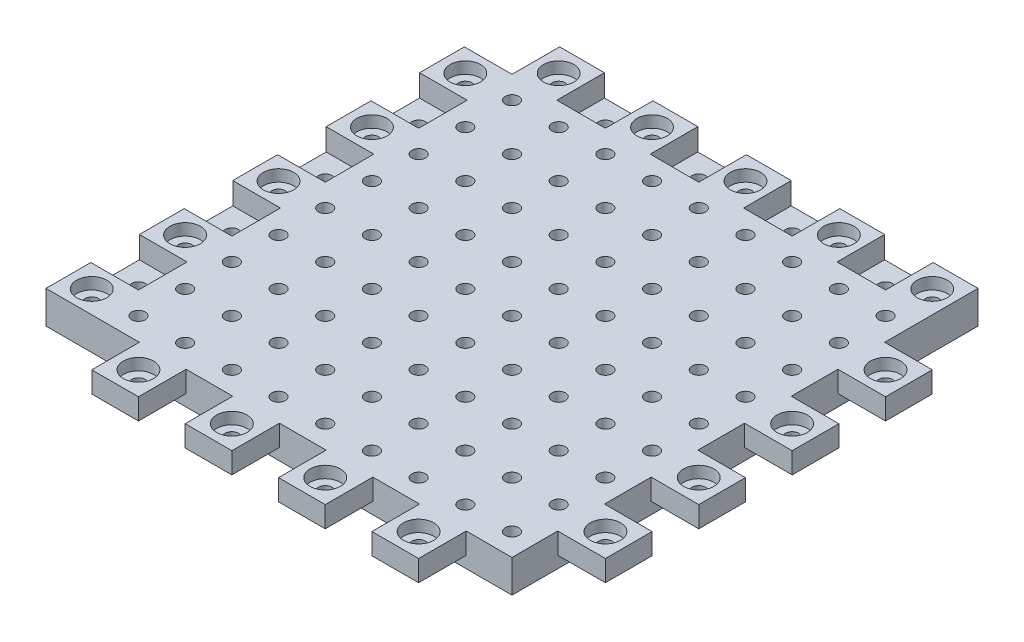
SolidWorks part; units mm, degrees
ref_plane "Alzado" through (0, 0, 0) normal (0, 0, 1) x (1, 0, 0)
ref_plane "Planta" through (0, 0, 0) normal (0, 1, 0) x (1, 0, 0)
ref_plane "Vista lateral" through (0, 0, 0) normal (1, 0, 0) x (0, 0, -1)
sketch "Croquis1" plane through (0, 0, 0) normal (0, 1, 0) x (1, 0, 0)
  line L1 (-50, -50) -> (50, -50)
  line L2 (-50, -50) -> (-50, 50)
  line L3 (-50, 50) -> (50, 50)
  line L4 (50, -50) -> (50, 50)
  line L5 (-50, -50) -> (50, 50) construction
  line L6 (-50, 50) -> (50, -50) construction
  point P0 (0, 0)
  dimension "D1" = 100
  dimension "D2" = 100
extrude "Saliente-Extruir1" add sketch "Croquis1" along normal blind 7
sketch "Croquis2" plane through (0, 7, 0) normal (0, 1, 0) x (1, 0, 0)
  line L45 (-50, 50) -> (-50, -50) construction
  line L50 (-50.2, 50.2) -> (-39.8, 50.2)
  line L55 (-50.2, 50.2) -> (-50.2, 39.8)
  line L60 (-50.2, 39.8) -> (-39.8, 39.8)
  line L65 (-39.8, 50.2) -> (-39.8, 39.8)
  line L70 (50, 50) -> (-50, 50) construction
  line L75 (-30.2, 50.2) -> (-19.8, 50.2)
  line L80 (-30.2, 50.2) -> (-30.2, 39.8)
  line L85 (-30.2, 39.8) -> (-19.8, 39.8)
  line L95 (-19.8, 50.2) -> (-19.8, 39.8)
  line L96 (-10.2, 50.2) -> (0.2, 50.2)
  line L97 (-10.2, 50.2) -> (-10.2, 39.8)
  line L98 (-10.2, 39.8) -> (0.2, 39.8)
  line L99 (0.2, 50.2) -> (0.2, 39.8)
  line L100 (9.8, 50.2) -> (20.2, 50.2)
  line L101 (9.8, 50.2) -> (9.8, 39.8)
  line L102 (9.8, 39.8) -> (20.2, 39.8)
  line L103 (20.2, 50.2) -> (20.2, 39.8)
  line L104 (29.8, 50.2) -> (40.2, 50.2)
  line L105 (29.8, 50.2) -> (29.8, 39.8)
  line L106 (29.8, 39.8) -> (40.2, 39.8)
  line L107 (40.2, 50.2) -> (40.2, 39.8)
  line L108 (-50.2, 30.2) -> (-39.8, 30.2)
  line L109 (-50.2, 30.2) -> (-50.2, 19.8)
  line L110 (-50.2, 19.8) -> (-39.8, 19.8)
  line L111 (-39.8, 30.2) -> (-39.8, 19.8)
  line L112 (-50.2, 10.2) -> (-39.8, 10.2)
  line L113 (-50.2, 10.2) -> (-50.2, -0.2)
  line L114 (-50.2, -0.2) -> (-39.8, -0.2)
  line L115 (-39.8, 10.2) -> (-39.8, -0.2)
  line L116 (-50.2, -9.8) -> (-39.8, -9.8)
  line L117 (-50.2, -9.8) -> (-50.2, -20.2)
  line L118 (-50.2, -20.2) -> (-39.8, -20.2)
  line L119 (-39.8, -9.8) -> (-39.8, -20.2)
  line L120 (-50.2, -29.8) -> (-39.8, -29.8)
  line L121 (-50.2, -29.8) -> (-50.2, -40.2)
  line L122 (-50.2, -40.2) -> (-39.8, -40.2)
  line L123 (-39.8, -29.8) -> (-39.8, -40.2)
  dimension "D3" = 0.2
  dimension "D1" = 10.4
  dimension "D2" = 10.4
  dimension "D4" = 0.2
  dimension "D5" = 5
extrude "Cortar-Extruir1" cut sketch "Croquis2" against normal blind 4.7
sketch "Croquis3" plane through (0, 7, 0) normal (0, 1, 0) x (1, 0, 0)
  line L0 (50, 30) -> (60, 30)
  line L5 (50, 50) -> (60, 50)
  line L6 (50, 50) -> (50, 40)
  line L7 (50, 40) -> (60, 40)
  line L8 (60, 50) -> (60, 40)
  line L9 (50, 30) -> (50, 20)
  line L10 (50, 20) -> (60, 20)
  line L11 (60, 30) -> (60, 20)
  line L12 (50, 10) -> (60, 10)
  line L13 (50, 10) -> (50, 0)
  line L14 (50, 0) -> (60, 0)
  line L15 (60, 10) -> (60, 0)
  line L16 (50, -10) -> (60, -10)
  line L17 (50, -10) -> (50, -20)
  line L18 (50, -20) -> (60, -20)
  line L19 (60, -10) -> (60, -20)
  line L20 (50, -30) -> (60, -30)
  line L21 (50, -30) -> (50, -40)
  line L22 (50, -40) -> (60, -40)
  line L23 (60, -30) -> (60, -40)
  line L24 (-30, -50) -> (-20, -50)
  line L25 (-50, -50) -> (-40, -50)
  line L26 (-50, -50) -> (-50, -60)
  line L27 (-50, -60) -> (-40, -60)
  line L28 (-40, -50) -> (-40, -60)
  line L29 (-30, -50) -> (-30, -60)
  line L30 (-30, -60) -> (-20, -60)
  line L31 (-20, -50) -> (-20, -60)
  line L32 (-10, -50) -> (0, -50)
  line L33 (-10, -50) -> (-10, -60)
  line L34 (-10, -60) -> (0, -60)
  line L35 (0, -50) -> (0, -60)
  line L36 (10, -50) -> (20, -50)
  line L37 (10, -50) -> (10, -60)
  line L38 (10, -60) -> (20, -60)
  line L39 (20, -50) -> (20, -60)
  line L40 (30, -50) -> (40, -50)
  line L41 (30, -50) -> (30, -60)
  line L42 (30, -60) -> (40, -60)
  line L43 (40, -50) -> (40, -60)
  dimension "D1" = 10
  dimension "D2" = 10
  dimension "D4" = 10
  dimension "D5" = 10
  dimension "D3" = 5
extrude "Saliente-Extruir2" add sketch "Croquis3" against normal blind 4.5
sketch "Croquis4" plane through (0, 7, 0) normal (0, 1, 0) x (1, 0, 0)
  line L0 (60, 45) -> (-63.1643, 45) construction
  line L1 (60, 40) -> (60, 50) construction
  line L2 (-45, -60) -> (-45, 61.9533) construction
  line L3 (-50, -60) -> (-40, -60) construction
  circle A0 centre (-45, 45) radius 1.45
  circle A1 centre (-35, 45) radius 1.45
  circle A2 centre (-25, 45) radius 1.45
  circle A3 centre (-15, 45) radius 1.45
  circle A4 centre (-5, 45) radius 1.45
  circle A5 centre (5, 45) radius 1.45
  circle A6 centre (15, 45) radius 1.45
  circle A7 centre (25, 45) radius 1.45
  circle A8 centre (35, 45) radius 1.45
  circle A9 centre (45, 45) radius 1.45
  circle A10 centre (55, 45) radius 1.45
  circle A11 centre (-35, 35) radius 1.45
  circle A12 centre (-25, 35) radius 1.45
  circle A13 centre (-15, 35) radius 1.45
  circle A14 centre (-5, 35) radius 1.45
  circle A15 centre (5, 35) radius 1.45
  circle A16 centre (15, 35) radius 1.45
  circle A17 centre (25, 35) radius 1.45
  circle A18 centre (35, 35) radius 1.45
  circle A19 centre (45, 35) radius 1.45
  circle A20 centre (55, 35) radius 1.45
  circle A21 centre (-35, 25) radius 1.45
  circle A22 centre (-25, 25) radius 1.45
  circle A23 centre (-15, 25) radius 1.45
  circle A24 centre (-5, 25) radius 1.45
  circle A25 centre (5, 25) radius 1.45
  circle A26 centre (15, 25) radius 1.45
  circle A27 centre (25, 25) radius 1.45
  circle A28 centre (35, 25) radius 1.45
  circle A29 centre (45, 25) radius 1.45
  circle A30 centre (55, 25) radius 1.45
  circle A31 centre (-35, 15) radius 1.45
  circle A32 centre (-25, 15) radius 1.45
  circle A33 centre (-15, 15) radius 1.45
  circle A34 centre (-5, 15) radius 1.45
  circle A35 centre (5, 15) radius 1.45
  circle A36 centre (15, 15) radius 1.45
  circle A37 centre (25, 15) radius 1.45
  circle A38 centre (35, 15) radius 1.45
  circle A39 centre (45, 15) radius 1.45
  circle A40 centre (55, 15) radius 1.45
  circle A41 centre (-35, 5) radius 1.45
  circle A42 centre (-25, 5) radius 1.45
  circle A43 centre (-15, 5) radius 1.45
  circle A44 centre (-5, 5) radius 1.45
  circle A45 centre (5, 5) radius 1.45
  circle A46 centre (15, 5) radius 1.45
  circle A47 centre (25, 5) radius 1.45
  circle A48 centre (35, 5) radius 1.45
  circle A49 centre (45, 5) radius 1.45
  circle A50 centre (55, 5) radius 1.45
  circle A51 centre (-35, -5) radius 1.45
  circle A52 centre (-25, -5) radius 1.45
  circle A53 centre (-15, -5) radius 1.45
  circle A54 centre (-5, -5) radius 1.45
  circle A55 centre (5, -5) radius 1.45
  circle A56 centre (15, -5) radius 1.45
  circle A57 centre (25, -5) radius 1.45
  circle A58 centre (35, -5) radius 1.45
  circle A59 centre (45, -5) radius 1.45
  circle A60 centre (55, -5) radius 1.45
  circle A61 centre (-35, -15) radius 1.45
  circle A62 centre (-25, -15) radius 1.45
  circle A63 centre (-15, -15) radius 1.45
  circle A64 centre (-5, -15) radius 1.45
  circle A65 centre (5, -15) radius 1.45
  circle A66 centre (15, -15) radius 1.45
  circle A67 centre (25, -15) radius 1.45
  circle A68 centre (35, -15) radius 1.45
  circle A69 centre (45, -15) radius 1.45
  circle A70 centre (55, -15) radius 1.45
  circle A71 centre (-35, -25) radius 1.45
  circle A72 centre (-25, -25) radius 1.45
  circle A73 centre (-15, -25) radius 1.45
  circle A74 centre (-5, -25) radius 1.45
  circle A75 centre (5, -25) radius 1.45
  circle A76 centre (15, -25) radius 1.45
  circle A77 centre (25, -25) radius 1.45
  circle A78 centre (35, -25) radius 1.45
  circle A79 centre (45, -25) radius 1.45
  circle A80 centre (55, -25) radius 1.45
  circle A81 centre (-35, -35) radius 1.45
  circle A82 centre (-25, -35) radius 1.45
  circle A83 centre (-15, -35) radius 1.45
  circle A84 centre (-5, -35) radius 1.45
  circle A85 centre (5, -35) radius 1.45
  circle A86 centre (15, -35) radius 1.45
  circle A87 centre (25, -35) radius 1.45
  circle A88 centre (35, -35) radius 1.45
  circle A89 centre (45, -35) radius 1.45
  circle A90 centre (55, -35) radius 1.45
  circle A91 centre (-35, -45) radius 1.45
  circle A92 centre (-25, -45) radius 1.45
  circle A93 centre (-15, -45) radius 1.45
  circle A94 centre (-5, -45) radius 1.45
  circle A95 centre (5, -45) radius 1.45
  circle A96 centre (15, -45) radius 1.45
  circle A97 centre (25, -45) radius 1.45
  circle A98 centre (35, -45) radius 1.45
  circle A99 centre (45, -45) radius 1.45
  circle A100 centre (55, -45) radius 1.45
  circle A101 centre (-35, -55) radius 1.45
  circle A102 centre (-25, -55) radius 1.45
  circle A103 centre (-15, -55) radius 1.45
  circle A104 centre (-5, -55) radius 1.45
  circle A105 centre (5, -55) radius 1.45
  circle A106 centre (15, -55) radius 1.45
  circle A107 centre (25, -55) radius 1.45
  circle A108 centre (35, -55) radius 1.45
  circle A109 centre (45, -55) radius 1.45
  circle A110 centre (55, -55) radius 1.45
  circle A111 centre (-45, 35) radius 1.45
  circle A112 centre (-45, 25) radius 1.45
  circle A113 centre (-45, 15) radius 1.45
  circle A114 centre (-45, 5) radius 1.45
  circle A115 centre (-45, -5) radius 1.45
  circle A116 centre (-45, -15) radius 1.45
  circle A117 centre (-45, -25) radius 1.45
  circle A118 centre (-45, -35) radius 1.45
  circle A119 centre (-45, -45) radius 1.45
  circle A120 centre (-45, -55) radius 1.45
  dimension "D1" = 2.9
  dimension "D2" = 11
extrude "Cortar-Extruir2" cut sketch "Croquis4" against normal blind 7
sketch "Croquis5" plane through (0, 7, 0) normal (0, 1, 0) x (1, 0, 0)
  circle A0 centre (-45, 45) radius 3.25
  circle A1 centre (-35, 45) radius 3.25
  circle A2 centre (-25, 45) radius 3.25
  circle A3 centre (-15, 45) radius 3.25
  circle A4 centre (-5, 45) radius 3.25
  circle A5 centre (5, 45) radius 3.25
  circle A6 centre (15, 45) radius 3.25
  circle A7 centre (25, 45) radius 3.25
  circle A8 centre (35, 45) radius 3.25
  circle A9 centre (45, 45) radius 3.25
  circle A10 centre (55, 45) radius 3.25
  circle A20 centre (55, 35) radius 3.25
  circle A30 centre (55, 25) radius 3.25
  circle A40 centre (55, 15) radius 3.25
  circle A50 centre (55, 5) radius 3.25
  circle A60 centre (55, -5) radius 3.25
  circle A70 centre (55, -15) radius 3.25
  circle A80 centre (55, -25) radius 3.25
  circle A90 centre (55, -35) radius 3.25
  circle A100 centre (55, -45) radius 3.25
  circle A101 centre (-35, -55) radius 3.25
  circle A102 centre (-25, -55) radius 3.25
  circle A103 centre (-15, -55) radius 3.25
  circle A104 centre (-5, -55) radius 3.25
  circle A105 centre (5, -55) radius 3.25
  circle A106 centre (15, -55) radius 3.25
  circle A107 centre (25, -55) radius 3.25
  circle A108 centre (35, -55) radius 3.25
  circle A109 centre (45, -55) radius 3.25
  circle A110 centre (55, -55) radius 3.25
  circle A111 centre (-45, 35) radius 3.25
  circle A112 centre (-45, 25) radius 3.25
  circle A113 centre (-45, 15) radius 3.25
  circle A114 centre (-45, 5) radius 3.25
  circle A115 centre (-45, -5) radius 3.25
  circle A116 centre (-45, -15) radius 3.25
  circle A117 centre (-45, -25) radius 3.25
  circle A118 centre (-45, -35) radius 3.25
  circle A119 centre (-45, -45) radius 3.25
  circle A120 centre (-45, -55) radius 3.25
  circle A121 centre (-35, 35) radius 3.25 [skipped]
  circle A122 centre (-25, 35) radius 3.25 [skipped]
  circle A123 centre (-15, 35) radius 3.25 [skipped]
  circle A124 centre (-5, 35) radius 3.25 [skipped]
  circle A125 centre (5, 35) radius 3.25 [skipped]
  circle A126 centre (15, 35) radius 3.25 [skipped]
  circle A127 centre (25, 35) radius 3.25 [skipped]
  circle A128 centre (35, 35) radius 3.25 [skipped]
  circle A129 centre (45, 35) radius 3.25 [skipped]
  circle A130 centre (-35, 25) radius 3.25 [skipped]
  circle A131 centre (-25, 25) radius 3.25 [skipped]
  circle A132 centre (-15, 25) radius 3.25 [skipped]
  circle A133 centre (-5, 25) radius 3.25 [skipped]
  circle A134 centre (5, 25) radius 3.25 [skipped]
  circle A135 centre (15, 25) radius 3.25 [skipped]
  circle A136 centre (25, 25) radius 3.25 [skipped]
  circle A137 centre (35, 25) radius 3.25 [skipped]
  circle A138 centre (45, 25) radius 3.25 [skipped]
  circle A139 centre (-35, 15) radius 3.25 [skipped]
  circle A140 centre (-25, 15) radius 3.25 [skipped]
  circle A141 centre (-15, 15) radius 3.25 [skipped]
  circle A142 centre (-5, 15) radius 3.25 [skipped]
  circle A143 centre (5, 15) radius 3.25 [skipped]
  circle A144 centre (15, 15) radius 3.25 [skipped]
  circle A145 centre (25, 15) radius 3.25 [skipped]
  circle A146 centre (35, 15) radius 3.25 [skipped]
  circle A147 centre (45, 15) radius 3.25 [skipped]
  circle A148 centre (-35, 5) radius 3.25 [skipped]
  circle A149 centre (-25, 5) radius 3.25 [skipped]
  circle A150 centre (-15, 5) radius 3.25 [skipped]
  circle A151 centre (-5, 5) radius 3.25 [skipped]
  circle A152 centre (5, 5) radius 3.25 [skipped]
  circle A153 centre (15, 5) radius 3.25 [skipped]
  circle A154 centre (25, 5) radius 3.25 [skipped]
  circle A155 centre (35, 5) radius 3.25 [skipped]
  circle A156 centre (45, 5) radius 3.25 [skipped]
  circle A157 centre (-35, -5) radius 3.25 [skipped]
  circle A158 centre (-25, -5) radius 3.25 [skipped]
  circle A159 centre (-15, -5) radius 3.25 [skipped]
  circle A160 centre (-5, -5) radius 3.25 [skipped]
  circle A161 centre (5, -5) radius 3.25 [skipped]
  circle A162 centre (15, -5) radius 3.25 [skipped]
  circle A163 centre (25, -5) radius 3.25 [skipped]
  circle A164 centre (35, -5) radius 3.25 [skipped]
  circle A165 centre (45, -5) radius 3.25 [skipped]
  circle A166 centre (-35, -15) radius 3.25 [skipped]
  circle A167 centre (-25, -15) radius 3.25 [skipped]
  circle A168 centre (-15, -15) radius 3.25 [skipped]
  circle A169 centre (-5, -15) radius 3.25 [skipped]
  circle A170 centre (5, -15) radius 3.25 [skipped]
  circle A171 centre (15, -15) radius 3.25 [skipped]
  circle A172 centre (25, -15) radius 3.25 [skipped]
  circle A173 centre (35, -15) radius 3.25 [skipped]
  circle A174 centre (45, -15) radius 3.25 [skipped]
  circle A175 centre (-35, -25) radius 3.25 [skipped]
  circle A176 centre (-25, -25) radius 3.25 [skipped]
  circle A177 centre (-15, -25) radius 3.25 [skipped]
  circle A178 centre (-5, -25) radius 3.25 [skipped]
  circle A179 centre (5, -25) radius 3.25 [skipped]
  circle A180 centre (15, -25) radius 3.25 [skipped]
  circle A181 centre (25, -25) radius 3.25 [skipped]
  circle A182 centre (35, -25) radius 3.25 [skipped]
  circle A183 centre (45, -25) radius 3.25 [skipped]
  circle A184 centre (-35, -35) radius 3.25 [skipped]
  circle A185 centre (-25, -35) radius 3.25 [skipped]
  circle A186 centre (-15, -35) radius 3.25 [skipped]
  circle A187 centre (-5, -35) radius 3.25 [skipped]
  circle A188 centre (5, -35) radius 3.25 [skipped]
  circle A189 centre (15, -35) radius 3.25 [skipped]
  circle A190 centre (25, -35) radius 3.25 [skipped]
  circle A191 centre (35, -35) radius 3.25 [skipped]
  circle A192 centre (45, -35) radius 3.25 [skipped]
  circle A193 centre (-35, -45) radius 3.25 [skipped]
  circle A194 centre (-25, -45) radius 3.25 [skipped]
  circle A195 centre (-15, -45) radius 3.25 [skipped]
  circle A196 centre (-5, -45) radius 3.25 [skipped]
  circle A197 centre (5, -45) radius 3.25 [skipped]
  circle A198 centre (15, -45) radius 3.25 [skipped]
  circle A199 centre (25, -45) radius 3.25 [skipped]
  circle A200 centre (35, -45) radius 3.25 [skipped]
  circle A201 centre (45, -45) radius 3.25 [skipped]
  dimension "D1" = 6.5
  dimension "D3" = 11
  dimension "D2" = 11
extrude "Cortar-Extruir4" cut sketch "Croquis5" against normal blind 2.5
sketch "Croquis6" plane through (0, 7, 0) normal (0, 1, 0) x (1, 0, 0)
  line L0 (50, -50) -> (40, -50)
  line L1 (50, -50) -> (50, -49.8)
  line L2 (40, -50) -> (40, -49.8)
  line L3 (49.8, -49.8) -> (40, -49.8)
  line L4 (30, -50) -> (20, -50)
  line L5 (30, -50) -> (30, -49.8)
  line L6 (20, -50) -> (20, -49.8)
  line L7 (30, -49.8) -> (20, -49.8)
  line L8 (10, -50) -> (0, -50)
  line L9 (10, -50) -> (10, -49.8)
  line L10 (0, -50) -> (0, -49.8)
  line L11 (10, -49.8) -> (0, -49.8)
  line L12 (-10, -50) -> (-20, -50)
  line L13 (-10, -50) -> (-10, -49.8)
  line L14 (-20, -50) -> (-20, -49.8)
  line L15 (-10, -49.8) -> (-20, -49.8)
  line L16 (-30, -50) -> (-40, -50)
  line L17 (-30, -50) -> (-30, -49.8)
  line L18 (-40, -50) -> (-40, -49.8)
  line L19 (-30, -49.8) -> (-40, -49.8)
  line L20 (50, -49.8) -> (50, -40)
  line L22 (50, -40) -> (49.8, -40)
  line L23 (49.8, -49.8) -> (49.8, -40)
  line L24 (50, -29.8) -> (50, -20)
  line L25 (50, -29.8) -> (49.8, -29.8)
  line L26 (50, -20) -> (49.8, -20)
  line L27 (49.8, -29.8) -> (49.8, -20)
  line L28 (50, -9.8) -> (50, 0)
  line L29 (50, -9.8) -> (49.8, -9.8)
  line L30 (50, 0) -> (49.8, 0)
  line L31 (49.8, -9.8) -> (49.8, 0)
  line L32 (50, 10.2) -> (50, 20)
  line L33 (50, 10.2) -> (49.8, 10.2)
  line L34 (50, 20) -> (49.8, 20)
  line L35 (49.8, 10.2) -> (49.8, 20)
  line L36 (50, 30.2) -> (50, 40)
  line L37 (50, 30.2) -> (49.8, 30.2)
  line L38 (50, 40) -> (49.8, 40)
  line L39 (49.8, 30.2) -> (49.8, 40)
  dimension "D1" = 0.2
  dimension "D2" = 0.2
  dimension "D3" = 5
extrude "Cortar-Extruir5" cut sketch "Croquis6" against normal blind 7
sketch "Croquis8" plane through (0, 7, 0) normal (0, 1, 0) x (1, 0, 0)
  line L1 (49.8, 40) -> (60, 40)
  line L2 (49.8, 40) -> (49.8, 50)
  line L3 (49.8, 50) -> (60, 50)
  line L4 (60, 40) -> (60, 50)
extrude "Cortar-Extruir7" cut sketch "Croquis8" against normal blind 7
sketch "Croquis9" plane through (0, 0, 0) normal (0, -1, 0) x (1, 0, 0)
  line L0 (-40, 50) -> (-40, 49.8)
  line L1 (-40, 50) -> (-50.0122, 50)
  line L2 (-40, 49.8) -> (-50.0122, 49.8)
  line L3 (-50.0122, 50) -> (-50.0122, 49.8)
  line L4 (-20, 50) -> (-20, 49.8)
  line L5 (-20, 50) -> (-30.0122, 50)
  line L6 (-20, 49.8) -> (-30.0122, 49.8)
  line L7 (-30.0122, 50) -> (-30.0122, 49.8)
  line L8 (0, 50) -> (0, 49.8)
  line L9 (0, 50) -> (-10.0122, 50)
  line L10 (0, 49.8) -> (-10.0122, 49.8)
  line L11 (-10.0122, 50) -> (-10.0122, 49.8)
  line L12 (20, 50) -> (20, 49.8)
  line L13 (20, 50) -> (9.9878, 50)
  line L14 (20, 49.8) -> (9.9878, 49.8)
  line L15 (9.9878, 50) -> (9.9878, 49.8)
  line L16 (40, 50) -> (40, 49.8)
  line L17 (40, 50) -> (29.9878, 50)
  line L18 (40, 49.8) -> (29.9878, 49.8)
  line L19 (29.9878, 50) -> (29.9878, 49.8)
  line L20 (50, -20) -> (50, -30.2)
  line L21 (50, -20) -> (49.8, -20)
  line L22 (50, -30.2) -> (49.8, -30.2)
  line L23 (49.8, -20) -> (49.8, -30.2)
  line L24 (49.8, -50) -> (49.8, -30.2) construction
  line L25 (50, 0) -> (50, -10.2)
  line L26 (50, 0) -> (49.8, 0)
  line L27 (50, -10.2) -> (49.8, -10.2)
  line L28 (49.8, 0) -> (49.8, -10.2)
  line L29 (50, 20) -> (50, 9.8)
  line L30 (50, 20) -> (49.8, 20)
  line L31 (50, 9.8) -> (49.8, 9.8)
  line L32 (49.8, 20) -> (49.8, 9.8)
  line L33 (50, 40) -> (50, 29.8)
  line L34 (50, 40) -> (49.8, 40)
  line L35 (50, 29.8) -> (49.8, 29.8)
  line L36 (49.8, 40) -> (49.8, 29.8)
  dimension "D1" = 0
  dimension "D2" = 4
extrude "Cortar-Extruir9" cut sketch "Croquis9" against normal blind 2.5
sketch "Croquis10" plane through (0, 2.5, 0) normal (0, -1, 0) x (1, 0, 0)
  line L0 (50, 30) -> (50, 29.8)
  line L1 (50, 30) -> (49.8, 30)
  line L2 (50, 29.8) -> (49.8, 29.8)
  line L3 (49.8, 30) -> (49.8, 29.8)
  line L4 (50, 10) -> (50, 9.8)
  line L5 (50, 10) -> (49.8, 10)
  line L6 (49.8, 10) -> (49.8, 9.8)
  line L7 (50, 9.8) -> (49.8, 9.8)
  line L8 (50, -10) -> (50, -10.2)
  line L9 (50, -10) -> (49.8, -10)
  line L10 (49.8, -10) -> (49.8, -10.2)
  line L11 (50, -10.2) -> (49.8, -10.2)
  line L12 (50, -30) -> (50, -30.2)
  line L13 (50, -30) -> (49.8, -30)
  line L14 (49.8, -30) -> (49.8, -30.2)
  line L15 (50, -30.2) -> (49.8, -30.2)
  line L16 (49.8, -20) -> (49.8, -30.2) construction
  dimension "D2" = 0
  dimension "D1" = 4
extrude "Cortar-Extruir11" cut sketch "Croquis10" against normal blind 5
sketch "Croquis11" plane through (0, 7, 0) normal (0, 1, 0) x (1, 0, 0)
  line L1 (-50, -60) -> (-40, -60)
  line L2 (-50, -60) -> (-50, -49.8)
  line L3 (-50, -49.8) -> (-40, -49.8)
  line L4 (-40, -60) -> (-40, -49.8)
  line L5 (-50, 50) -> (-39.8, 50)
  line L6 (-50, 50) -> (-50, 39.8)
  line L7 (-50, 39.8) -> (-39.8, 39.8)
  line L8 (-39.8, 50) -> (-39.8, 39.8)
extrude "Cortar-Extruir12" cut sketch "Croquis11" against normal blind 10
